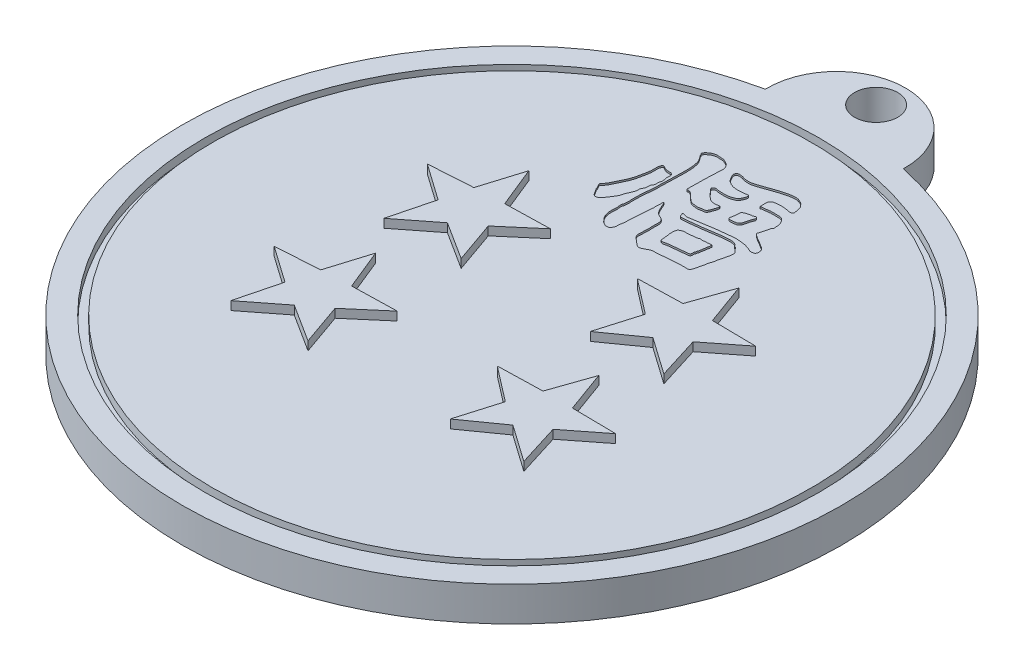
SolidWorks part; units mm, degrees
ref_plane "Front Plane" through (0, 0, 0) normal (0, 0, 1) x (1, 0, 0)
ref_plane "Top Plane" through (0, 0, 0) normal (0, 1, 0) x (1, 0, 0)
ref_plane "Right Plane" through (0, 0, 0) normal (1, 0, 0) x (0, 0, -1)
sketch "Sketch1" plane through (0, 0, 0) normal (0, 1, 0) x (1, 0, 0)
  line L0 (72.6998, 334.9365) -> (606.0331, 334.9365) construction
  line L11 (9.9855, -19.0663) -> (11.8306, -12.8124)
  line L12 (11.8306, -12.8124) -> (6.6838, -8.8503)
  line L13 (6.6838, -8.8503) -> (13.2484, -8.6755)
  line L14 (13.2484, -8.6755) -> (15.3732, -2.5828)
  line L15 (15.3732, -2.5828) -> (17.5873, -8.6755)
  line L16 (17.5873, -8.6755) -> (24.0432, -8.7629)
  line L17 (24.0432, -8.7629) -> (18.8692, -12.8124)
  line L18 (18.8692, -12.8124) -> (20.8153, -19.0663)
  line L19 (20.8153, -19.0663) -> (15.3732, -15.2382)
  line L20 (15.3732, -15.2382) -> (9.9855, -19.0663)
  line L21 (-4.1182, 14.4191) -> (1.9132, 14.499) construction
  line L22 (-1.1025, 14.459) -> (0, -28.999) construction
  line L33 (-21.2921, -20.1346) -> (-16.0512, -16.0354)
  line L34 (-19.6657, -13.79) -> (-21.2921, -20.1346)
  line L35 (-25.0384, -10.0081) -> (-19.6657, -13.79)
  line L36 (-18.5952, -9.5934) -> (-25.0384, -10.0081)
  line L37 (-16.6929, -3.3963) -> (-18.5952, -9.5934)
  line L38 (-14.2619, -9.3734) -> (-16.6929, -3.3963)
  line L39 (-7.6968, -9.2151) -> (-14.2619, -9.3734)
  line L40 (-12.6361, -13.4331) -> (-7.6968, -9.2151)
  line L41 (-10.4763, -19.5854) -> (-12.6361, -13.4331)
  line L42 (-16.0512, -16.0354) -> (-10.4763, -19.5854)
  line L43 (9.1329, 2.4208) -> (10.978, 8.6747)
  line L44 (10.978, 8.6747) -> (5.8312, 12.6368)
  line L45 (5.8312, 12.6368) -> (12.3958, 12.8116)
  line L46 (12.3958, 12.8116) -> (14.5206, 18.9043)
  line L47 (14.5206, 18.9043) -> (16.7347, 12.8116)
  line L48 (16.7347, 12.8116) -> (23.1906, 12.7242)
  line L49 (23.1906, 12.7242) -> (18.0166, 8.6747)
  line L50 (18.0166, 8.6747) -> (19.9627, 2.4208)
  line L51 (19.9627, 2.4208) -> (14.5206, 6.2489)
  line L52 (14.5206, 6.2489) -> (9.1329, 2.4208)
  line L53 (-20.5145, 1.6585) -> (-15.2735, 5.7576)
  line L54 (-18.888, 8.0031) -> (-20.5145, 1.6585)
  line L55 (-24.2607, 11.785) -> (-18.888, 8.0031)
  line L56 (-17.8175, 12.1996) -> (-24.2607, 11.785)
  line L57 (-15.9152, 18.3968) -> (-17.8175, 12.1996)
  line L58 (-13.4842, 12.4197) -> (-15.9152, 18.3968)
  line L59 (-6.9191, 12.5779) -> (-13.4842, 12.4197)
  line L60 (-11.8585, 8.36) -> (-6.9191, 12.5779)
  line L61 (-9.6986, 2.2076) -> (-11.8585, 8.36)
  line L62 (-15.2735, 5.7576) -> (-9.6986, 2.2076)
  circle A0 centre (0, 0) radius 48.586
  circle A1 centre (0, 0) radius 45.2612
  point P6 (0, 0)
  point P32 (0, -28.999)
sketch "Sketch2" plane through (0, 0, 0) normal (0, 1, 0) x (1, 0, 0)
  circle A0 centre (0, 0) radius 48.586 construction
  circle A1 centre (0, 0) radius 48.586
extrude "Boss-Extrude1" add sketch "Sketch2" along normal blind 5.08 contours A1
sketch "Sketch3" plane through (0, 5.08, 0) normal (0, 1, 0) x (1, 0, 0)
  circle A0 centre (0, 0) radius 44.1145 construction
  circle A1 centre (0, 0) radius 45.2612 construction
  circle A2 centre (0, 0) radius 44.1145
  circle A3 centre (0, 0) radius 45.2612
extrude "Cut-Extrude1" cut sketch "Sketch3" against normal blind 1.27
sketch "Sketch5" plane through (0, 5.08, 0) normal (0, 1, 0) x (1, 0, 0)
  line L0 (19.9627, 2.4208) -> (14.5206, 6.2489) construction
  line L1 (18.0166, 8.6747) -> (19.9627, 2.4208) construction
  line L2 (23.1906, 12.7242) -> (18.0166, 8.6747) construction
  line L3 (16.7347, 12.8116) -> (23.1906, 12.7242) construction
  line L4 (14.5206, 18.9043) -> (16.7347, 12.8116) construction
  line L5 (12.3958, 12.8116) -> (14.5206, 18.9043) construction
  line L6 (5.8312, 12.6368) -> (12.3958, 12.8116) construction
  line L7 (10.978, 8.6747) -> (5.8312, 12.6368) construction
  line L8 (9.1329, 2.4208) -> (10.978, 8.6747) construction
  line L9 (14.5206, 6.2489) -> (9.1329, 2.4208) construction
  line L10 (13.2484, -8.6755) -> (15.3732, -2.5828) construction
  line L11 (15.3732, -2.5828) -> (17.5873, -8.6755) construction
  line L12 (17.5873, -8.6755) -> (24.0432, -8.7629) construction
  line L13 (24.0432, -8.7629) -> (18.8692, -12.8124) construction
  line L14 (18.8692, -12.8124) -> (20.8153, -19.0663) construction
  line L15 (20.8153, -19.0663) -> (15.3732, -15.2382) construction
  line L16 (15.3732, -15.2382) -> (9.9855, -19.0663) construction
  line L17 (9.9855, -19.0663) -> (11.8306, -12.8124) construction
  line L18 (11.8306, -12.8124) -> (6.6838, -8.8503) construction
  line L19 (6.6838, -8.8503) -> (13.2484, -8.6755) construction
  line L20 (-7.6968, -9.2151) -> (-14.2619, -9.3734) construction
  line L21 (-12.6361, -13.4331) -> (-7.6968, -9.2151) construction
  line L22 (-10.4763, -19.5854) -> (-12.6361, -13.4331) construction
  line L23 (-16.0512, -16.0354) -> (-10.4763, -19.5854) construction
  line L24 (-21.2921, -20.1346) -> (-16.0512, -16.0354) construction
  line L25 (-19.6657, -13.79) -> (-21.2921, -20.1346) construction
  line L26 (-25.0384, -10.0081) -> (-19.6657, -13.79) construction
  line L27 (-18.5952, -9.5934) -> (-25.0384, -10.0081) construction
  line L28 (-16.6929, -3.3963) -> (-18.5952, -9.5934) construction
  line L29 (-14.2619, -9.3734) -> (-16.6929, -3.3963) construction
  line L30 (-15.2735, 5.7576) -> (-9.6986, 2.2076) construction
  line L31 (-9.6986, 2.2076) -> (-11.8585, 8.36) construction
  line L32 (-11.8585, 8.36) -> (-6.9191, 12.5779) construction
  line L33 (-6.9191, 12.5779) -> (-13.4842, 12.4197) construction
  line L34 (-13.4842, 12.4197) -> (-15.9152, 18.3968) construction
  line L35 (-15.9152, 18.3968) -> (-17.8175, 12.1996) construction
  line L36 (-17.8175, 12.1996) -> (-24.2607, 11.785) construction
  line L37 (-24.2607, 11.785) -> (-18.888, 8.0031) construction
  line L38 (-18.888, 8.0031) -> (-20.5145, 1.6585) construction
  line L39 (-20.5145, 1.6585) -> (-15.2735, 5.7576) construction
  line L40 (19.9627, 2.4208) -> (14.5206, 6.2489)
  line L41 (18.0166, 8.6747) -> (19.9627, 2.4208)
  line L42 (23.1906, 12.7242) -> (18.0166, 8.6747)
  line L43 (16.7347, 12.8116) -> (23.1906, 12.7242)
  line L44 (14.5206, 18.9043) -> (16.7347, 12.8116)
  line L45 (12.3958, 12.8116) -> (14.5206, 18.9043)
  line L46 (5.8312, 12.6368) -> (12.3958, 12.8116)
  line L47 (10.978, 8.6747) -> (5.8312, 12.6368)
  line L48 (9.1329, 2.4208) -> (10.978, 8.6747)
  line L49 (14.5206, 6.2489) -> (9.1329, 2.4208)
  line L50 (13.2484, -8.6755) -> (15.3732, -2.5828)
  line L51 (15.3732, -2.5828) -> (17.5873, -8.6755)
  line L52 (17.5873, -8.6755) -> (24.0432, -8.7629)
  line L53 (24.0432, -8.7629) -> (18.8692, -12.8124)
  line L54 (18.8692, -12.8124) -> (20.8153, -19.0663)
  line L55 (20.8153, -19.0663) -> (15.3732, -15.2382)
  line L56 (15.3732, -15.2382) -> (9.9855, -19.0663)
  line L57 (9.9855, -19.0663) -> (11.8306, -12.8124)
  line L58 (11.8306, -12.8124) -> (6.6838, -8.8503)
  line L59 (6.6838, -8.8503) -> (13.2484, -8.6755)
  line L60 (-7.6968, -9.2151) -> (-14.2619, -9.3734)
  line L61 (-12.6361, -13.4331) -> (-7.6968, -9.2151)
  line L62 (-10.4763, -19.5854) -> (-12.6361, -13.4331)
  line L63 (-16.0512, -16.0354) -> (-10.4763, -19.5854)
  line L64 (-21.2921, -20.1346) -> (-16.0512, -16.0354)
  line L65 (-19.6657, -13.79) -> (-21.2921, -20.1346)
  line L66 (-25.0384, -10.0081) -> (-19.6657, -13.79)
  line L67 (-18.5952, -9.5934) -> (-25.0384, -10.0081)
  line L68 (-16.6929, -3.3963) -> (-18.5952, -9.5934)
  line L69 (-14.2619, -9.3734) -> (-16.6929, -3.3963)
  line L70 (-15.2735, 5.7576) -> (-9.6986, 2.2076)
  line L71 (-9.6986, 2.2076) -> (-11.8585, 8.36)
  line L72 (-11.8585, 8.36) -> (-6.9191, 12.5779)
  line L73 (-6.9191, 12.5779) -> (-13.4842, 12.4197)
  line L74 (-13.4842, 12.4197) -> (-15.9152, 18.3968)
  line L75 (-15.9152, 18.3968) -> (-17.8175, 12.1996)
  line L76 (-17.8175, 12.1996) -> (-24.2607, 11.785)
  line L77 (-24.2607, 11.785) -> (-18.888, 8.0031)
  line L78 (-18.888, 8.0031) -> (-20.5145, 1.6585)
  line L79 (-20.5145, 1.6585) -> (-15.2735, 5.7576)
extrude "Boss-Extrude4" add sketch "Sketch5" along normal blind 1.27
sketch "Sketch6" plane through (0, 0, 0) normal (0, -1, 0) x (1, 0, 0)
  line L0 (0, 0) -> (0, -48.586) construction
  line L1 (0, -48.586) -> (0, -53.666) construction
  line L2 (10.16, -47.5119) -> (0, -48.586) construction
  line L3 (0, -48.586) -> (-10.16, -47.5119) construction
  circle A0 centre (0, 0) radius 48.586 construction
  circle A1 centre (0, -53.666) radius 3.175
  arc A2 (10.16, -47.5119) -> (-10.16, -47.5119) centre (0, -47.8316) cw
  circle M5 centre (0, 0) radius 48.586
  dimension "D1" = 6.35
  dimension "D4" = 10.165
  dimension "D2" = 5.08
  dimension "D3" = 10.16
extrude "Boss-Extrude5" add sketch "Sketch6" against normal up to surface (5.08 mm away) contours A2 A1 M5 up to face at (0, 5.08, 45.2612)
sketch "Sketch7" plane through (0, 5.08, 0) normal (0, 1, 0) x (1, 0, 0)
  line L0 (140.8867, 493.3987) -> (794.2201, 493.3987) construction
  spline S0 degree 3 poles (-3.7836, 35.2045) (-3.5089, 35.0981) (-3.2915, 34.8741) (-3.1389, 34.5991) (-3.0052, 34.177) (-3.1249, 33.6304) (-3.0644, 32.9308) (-3.1263, 32.1641) (-3.1777, 31.3954) (-3.1455, 30.6787) (-3.1644, 30.0405) (-3.1763, 29.4923) (-3.202, 29.1508) (-3.1534, 28.8256) (-2.9198, 28.9809) (-2.7009, 28.8609) (-2.4188, 28.7675) (-2.1857, 28.4675) (-1.8669, 28.2384) (-1.5861, 27.908) (-1.2854, 27.7054) (-0.9431, 27.5455) (-0.5328, 27.5044) (-0.031, 27.4441) (0.4097, 27.5927) (0.7344, 27.5886) (0.9698, 27.6572) (1.0884, 27.8586) (1.2713, 28.3125) (1.7457, 29.4886) (0.9478, 29.1003) (0.6202, 29.1708) (0.3204, 29.1642) (0.0135, 29.2701) (-0.3132, 29.5366) (-0.662, 29.8389) (-0.9763, 30.2207) (-1.2818, 30.496) (-1.4556, 30.7183) (-1.5899, 31.0316) (-1.3014, 31.0599) (-1.1735, 31.2344) (-0.8941, 31.1356) (-0.609, 31.1185) (-0.1231, 31.0805) (0.3708, 31.0664) (0.9699, 31.128) (1.3837, 31.3549) (1.7867, 31.4497) (2.0412, 31.9201) (2.4685, 32.8608) (1.639, 32.6288) (1.1004, 32.6586) (0.5295, 32.5597) (0.1059, 32.6315) (-0.1765, 32.6823) (-0.3604, 32.8178) (-0.586, 32.8277) (-0.6821, 33.011) (-0.9456, 33.0333) (-1.0927, 33.2692) (-1.3119, 33.483) (-1.3974, 33.7818) (-1.5697, 34.0046) (-1.6727, 34.2764) (-1.6204, 34.5866) (-1.3062, 34.7622) (-0.9871, 34.7165) (-0.5973, 34.6782) (-0.2544, 34.4887) (0.1677, 34.5192) (0.6049, 34.445) (1.107, 34.6293) (1.689, 34.7699) (2.3144, 35.028) (3.0022, 35.1982) (3.5819, 35.4539) (4.093, 35.6101) (4.528, 35.7079) (4.9831, 35.8469) (5.4125, 35.911) (5.8519, 35.9535) (6.2942, 35.9184) (6.6881, 35.7437) (7.0317, 35.5601) (7.2316, 35.3164) (7.4687, 35.0799) (7.5771, 34.7503) (7.6769, 34.4243) (7.6967, 34.1301) (7.7854, 33.8634) (7.6396, 33.7259) (7.511, 33.5979) (7.2893, 33.5981) (7.0031, 33.6726) (6.61, 33.7351) (6.1138, 33.7866) (5.6119, 33.7841) (5.2065, 33.7079) (4.9316, 33.7083) (4.7359, 33.658) (4.6548, 33.5059) (4.5413, 33.3836) (4.4021, 33.2285) (4.3935, 32.9984) (4.4246, 32.7765) (4.4008, 32.5136) (4.4427, 32.33) (4.3939, 32.0301) (4.6138, 32.2069) (4.8511, 32.1759) (5.1271, 32.2551) (5.4716, 32.2584) (5.7784, 32.3491) (6.2025, 32.3275) (6.592, 32.3161) (6.9492, 32.3163) (7.2031, 32.3201) (7.3884, 32.2565) (7.5948, 32.148) (7.7958, 31.9598) (7.9926, 31.6202) (8.1568, 31.284) (8.1937, 30.9204) (8.1837, 30.6376) (8.2599, 30.3373) (8.0223, 30.1491) (8.0065, 29.8231) (7.8875, 29.5105) (7.8495, 29.2056) (7.7193, 28.9715) (7.7212, 28.7417) (7.5927, 28.5614) (7.6486, 28.3243) (7.8482, 28.165) (8.1225, 28.0321) (8.3693, 27.8339) (8.6976, 27.6764) (9.0026, 27.4911) (9.2854, 27.3028) (9.5469, 27.134) (9.8317, 27.0114) (9.9823, 26.7634) (10.1584, 26.5687) (10.1041, 26.366) (10.2076, 26.1888) (10.1424, 25.9543) (10.0037, 25.7445) (9.6875, 25.6829) (9.3579, 25.6793) (9.0323, 25.8649) (8.6536, 25.9923) (8.2078, 26.1509) (7.6978, 26.2033) (7.231, 26.2679) (6.7409, 26.2982) (6.2694, 26.3102) (5.8148, 26.2001) (5.3369, 26.1804) (4.8125, 26.0902) (4.2287, 26.0241) (3.6571, 25.9649) (3.0068, 25.7729) (2.351, 25.7201) (1.6659, 25.6014) (1.1056, 25.4963) (0.5496, 25.4422) (0.1359, 25.3767) (-0.5654, 25.7212) (-0.3203, 25.3488) (-0.3219, 25.1436) (-0.1782, 25.0022) (0.0486, 24.9061) (0.371, 25.0185) (0.8278, 24.988) (1.3886, 25.0709) (2.01, 25.1408) (2.5683, 25.213) (3.1003, 25.2557) (3.613, 25.3782) (4.2241, 25.4428) (4.9256, 25.5576) (5.5898, 25.6342) (6.2127, 25.6733) (6.6591, 25.7001) (7.0265, 25.6562) (7.2948, 25.5264) (7.5452, 25.4097) (7.6448, 25.0287) (7.8517, 25.1977) (8.0341, 24.8026) (8.2776, 24.5969) (8.5994, 24.2972) (8.4928, 23.9664) (8.5302, 23.6729) (8.3886, 23.3897) (8.3664, 23.054) (8.2572, 22.7223) (8.1944, 22.3723) (8.0791, 22.0634) (8.0772, 21.7102) (7.9417, 21.3449) (7.8043, 20.9446) (7.7949, 20.4858) (7.626, 20.0909) (7.5704, 19.6728) (7.4456, 19.3466) (7.3976, 19.0119) (7.0875, 18.7779) (6.6061, 18.8696) (6.0046, 18.8325) (5.3649, 18.8274) (4.7751, 18.7542) (4.2395, 18.7201) (3.7264, 18.6612) (3.2156, 18.6669) (2.6512, 18.5363) (2.073, 18.6159) (1.5751, 18.3477) (1.2134, 18.1683) (0.8773, 17.9729) (0.476, 17.99) (0.1521, 18.2617) (-0.1789, 18.5315) (-0.4612, 18.7961) (-0.7369, 18.9744) (-0.8964, 19.2182) (-1.07, 19.5493) (-0.9938, 19.979) (-0.985, 20.6432) (-0.9358, 21.3081) (-1.0159, 22.0378) (-0.9547, 22.5103) (-0.9993, 22.9089) (-1.1533, 23.1813) (-1.4287, 23.3935) (-1.7581, 23.4837) (-2.0732, 23.675) (-2.3135, 23.8827) (-2.4297, 24.1145) (-2.5757, 24.3159) (-2.6661, 24.5097) (-2.7444, 24.7109) (-2.827, 24.86) (-2.9175, 25.033) (-2.9487, 25.2188) (-3.0507, 25.3649) (-3.0995, 25.4726) (-3.2008, 25.6233) (-3.2595, 25.3359) (-3.2231, 25.165) (-3.2783, 24.9198) (-3.239, 24.6957) (-3.3204, 24.4607) (-3.231, 24.2223) (-3.2847, 23.9347) (-3.2968, 23.6148) (-3.3631, 23.2553) (-3.3385, 22.9202) (-3.3955, 22.5735) (-3.3877, 22.2285) (-3.4402, 21.5667) (-3.5388, 20.9257) (-3.5077, 20.2114) (-3.5835, 19.7707) (-3.6865, 19.3421) (-3.6325, 18.9841) (-3.7267, 18.6813) (-3.9059, 18.5239) (-4.02, 18.3198) (-4.2673, 18.3193) (-4.5231, 18.2732) (-4.7611, 18.4038) (-4.951, 18.5168) (-5.1295, 18.6346) (-5.2659, 18.7905) (-5.4184, 18.9669) (-5.5883, 19.1346) (-5.7036, 19.3456) (-5.8201, 19.5258) (-5.8998, 19.6922) (-5.8811, 19.8482) (-5.985, 19.9875) (-6.0122, 20.188) (-6.0307, 20.3608) (-6.0475, 20.5815) (-6.0126, 20.8376) (-6.0503, 21.209) (-5.9529, 21.6587) (-6.1399, 22.0929) (-5.9551, 22.4219) (-5.951, 22.6953) (-5.9095, 22.9494) (-5.888, 23.2158) (-5.9588, 23.4669) (-5.921, 23.8135) (-5.9203, 24.232) (-5.8852, 24.7472) (-5.9388, 25.304) (-5.8255, 25.8185) (-5.7694, 26.2347) (-5.7937, 26.5924) (-5.707, 26.9982) (-5.7533, 27.425) (-5.7443, 27.945) (-5.7423, 28.586) (-5.6856, 29.3486) (-5.6956, 30.159) (-5.6354, 30.8559) (-5.6303, 31.5356) (-5.6898, 32.08) (-5.6925, 32.5715) (-5.8106, 32.9005) (-5.8158, 33.2034) (-5.9579, 33.3884) (-6.0124, 33.6001) (-6.1451, 33.7114) (-6.1636, 33.8538) (-6.3005, 33.9334) (-6.3532, 34.0964) (-6.4992, 34.2186) (-6.5145, 34.4046) (-6.7359, 34.5085) (-6.6201, 34.8362) (-6.4403, 35.0915) (-6.1304, 35.1585) (-5.9861, 35.3681) (-5.7104, 35.4732) (-5.2967, 35.5698) (-4.8338, 35.4962) (-4.3902, 35.5063) (-4.0435, 35.3811) (-3.7836, 35.2045) (-3.5089, 35.0981) (-3.2915, 34.8741) knots -0.007629 -0.004974 -0.00202 0 0.002078 0.00539 0.007596 0.012664 0.018527 0.024632 0.031294 0.037247 0.041978 0.046955 0.050054 0.051343 0.053087 0.05461 0.057236 0.060177 0.06353 0.066759 0.070627 0.072234 0.075881 0.080535 0.084354 0.086894 0.088469 0.089986 0.092213 0.101638 0.105781 0.107664 0.109953 0.112967 0.115302 0.120151 0.124134 0.127363 0.129875 0.131556 0.133822 0.134867 0.136425 0.139965 0.142254 0.148126 0.152082 0.15655 0.159796 0.161153 0.169822 0.172857 0.177924 0.183967 0.186354 0.188372 0.190856 0.191688 0.193598 0.195069 0.197606 0.199809 0.202509 0.204894 0.206583 0.209522 0.211524 0.214663 0.217116 0.221051 0.223752 0.227225 0.231645 0.236403 0.241837 0.248003 0.253567 0.257181 0.260963 0.264392 0.268722 0.271472 0.275121 0.279325 0.281865 0.284461 0.286912 0.289891 0.292722 0.29512 0.297256 0.298727 0.299588 0.301625 0.303558 0.306923 0.311207 0.315693 0.319066 0.321125 0.322475 0.323625 0.325105 0.326596 0.328508 0.330376 0.332145 0.334642 0.335779 0.33734 0.338801 0.341991 0.343955 0.347191 0.349623 0.354205 0.356668 0.358312 0.36033 0.361333 0.363972 0.366855 0.370855 0.372927 0.375596 0.377968 0.379514 0.382259 0.385407 0.387705 0.389614 0.391787 0.393047 0.394736 0.397051 0.399031 0.402158 0.404662 0.40785 0.410823 0.412897 0.415454 0.41807 0.419914 0.421322 0.422715 0.424585 0.426896 0.428359 0.432153 0.434642 0.437303 0.44187 0.446066 0.449702 0.453317 0.458004 0.461061 0.464615 0.469585 0.473968 0.47889 0.483506 0.490362 0.494819 0.500345 0.504389 0.507832 0.512267 0.51431 0.515379 0.517345 0.518646 0.521234 0.525112 0.529774 0.534928 0.540319 0.543444 0.547871 0.553084 0.558351 0.565136 0.569305 0.573514 0.575982 0.578211 0.580564 0.583245 0.58354 0.58645 0.589613 0.593116 0.595325 0.597453 0.600191 0.602709 0.605564 0.608626 0.611343 0.613481 0.617095 0.620709 0.623708 0.628093 0.630978 0.633875 0.636611 0.638852 0.642405 0.64787 0.653658 0.657868 0.662301 0.666688 0.670408 0.674644 0.680712 0.683893 0.688082 0.690648 0.693152 0.697251 0.700517 0.703608 0.706647 0.708327 0.710639 0.715525 0.718355 0.726893 0.731611 0.736104 0.738401 0.741236 0.743423 0.74668 0.749403 0.752349 0.754218 0.755643 0.758384 0.759377 0.760881 0.762523 0.764083 0.7654 0.766666 0.767317 0.768793 0.770742 0.772663 0.774459 0.776238 0.778438 0.780316 0.783233 0.786234 0.789139 0.791329 0.794733 0.797491 0.807452 0.810409 0.814791 0.818289 0.820977 0.823491 0.825536 0.826765 0.828815 0.83089 0.833058 0.835073 0.836341 0.838215 0.840064 0.842022 0.843972 0.845849 0.847283 0.848322 0.849473 0.851289 0.853142 0.85372 0.856658 0.859368 0.862718 0.867703 0.869532 0.871501 0.874238 0.875821 0.877931 0.880462 0.884195 0.888118 0.892988 0.897656 0.900826 0.903157 0.906314 0.910795 0.913484 0.918951 0.926355 0.932042 0.938613 0.943337 0.948511 0.951933 0.955159 0.956929 0.959081 0.960609 0.962114 0.963056 0.963808 0.965719 0.966996 0.968222 0.969897 0.971784 0.975261 0.977403 0.978925 0.981171 0.984323 0.989207 0.992371 0.995026 0.99798 1 1.002078 1.00539 1.007596 only from (-3.5208, 35.0839) to (-3.5208, 35.0839)
  spline S1 degree 3 poles (1.6683, 20.4631) (1.357, 20.55) (1.3868, 20.9287) (1.309, 21.2902) (1.3047, 21.6543) (1.2156, 21.9873) (1.2463, 22.2874) (1.1854, 22.5858) (1.298, 22.8281) (1.3278, 23.1183) (1.6221, 23.1562) (1.8189, 23.3631) (2.2465, 23.3511) (2.6933, 23.3214) (3.1364, 23.4183) (3.5113, 23.4616) (3.877, 23.4542) (4.2064, 23.692) (4.4631, 23.5047) (4.6995, 23.6032) (4.9347, 23.6277) (5.1929, 23.5991) (5.4145, 23.688) (5.6013, 23.677) (5.9143, 23.6652) (5.7283, 23.5369) (5.8184, 23.3552) (5.7491, 23.1584) (5.6881, 22.9472) (5.675, 22.7403) (5.634, 22.5249) (5.6248, 22.3466) (5.5851, 22.1818) (5.5616, 22.0752) (5.5766, 21.933) (5.4405, 21.8302) (5.5102, 21.629) (5.3727, 21.4889) (5.4006, 21.3199) (5.3966, 21.1721) (5.3875, 21.0087) (5.2266, 20.8849) (5.0156, 20.8795) (4.793, 20.8494) (4.5965, 20.8184) (4.3809, 20.796) (4.1137, 20.7483) (3.7805, 20.74) (3.3812, 20.714) (2.9745, 20.6222) (2.5576, 20.6221) (2.2222, 20.5578) (1.9218, 20.4682) (1.6683, 20.4631) (1.357, 20.55) (1.3868, 20.9287) knots -0.05572 -0.036145 -0.012641 0 0.027242 0.053189 0.084692 0.104414 0.12725 0.149766 0.167459 0.185378 0.204991 0.222213 0.244933 0.291565 0.32141 0.342232 0.373373 0.400527 0.417412 0.432728 0.452372 0.468795 0.488895 0.499368 0.517227 0.522976 0.536231 0.553033 0.567391 0.583902 0.597725 0.614924 0.62239 0.634482 0.638436 0.652552 0.663845 0.678607 0.689258 0.69905 0.711439 0.722438 0.739144 0.756259 0.771362 0.782217 0.803259 0.830087 0.854363 0.889936 0.920013 0.94428 0.963855 0.987359 1 1.027242 1.053189 1.084692 only from (1.4502, 20.5475) to (1.4502, 20.5475)
  spline S2 degree 3 poles (3.7659, 29.9366) (3.7729, 29.7303) (3.7595, 29.4543) (3.6984, 29.0897) (3.6684, 28.7571) (3.5673, 28.543) (3.5985, 28.3349) (3.9305, 28.1836) (4.3427, 28.3001) (5.2436, 28.3282) (5.3027, 29.3702) (5.5279, 29.9803) (5.6713, 30.2438) (5.6098, 30.527) (5.3123, 30.5722) (5.1516, 30.3567) (4.8902, 30.4065) (4.6131, 30.3027) (4.2696, 30.2408) (3.9573, 30.121) (3.7659, 29.9366) (3.7729, 29.7303) (3.7595, 29.4543) knots -0.097797 -0.033473 -0.003749 0 0.05317 0.1134 0.156634 0.193344 0.211968 0.238222 0.331273 0.3939 0.590806 0.651018 0.679964 0.716019 0.753906 0.77624 0.820726 0.850878 0.902203 0.966527 0.996251 1 1.05317 1.1134 1.156634 only from (3.7689, 29.848) to (3.7689, 29.848)
  spline S3 degree 3 poles (-8.7326, 21.2793) (-9.1077, 21.2895) (-9.4234, 21.4851) (-9.5985, 21.8878) (-9.9662, 22.3131) (-10.0718, 22.7968) (-10.381, 23.178) (-10.1515, 23.4996) (-9.7625, 23.8817) (-9.4152, 24.7778) (-8.8706, 25.7618) (-8.5332, 26.7663) (-8.3159, 27.7776) (-8.1524, 28.6636) (-8.1913, 29.4503) (-8.1612, 29.8861) (-7.9779, 30.3512) (-7.4671, 30.0245) (-7.0266, 29.8176) (-6.4912, 29.9361) (-5.9931, 29.6357) (-6.2309, 28.997) (-5.913, 28.3115) (-6.189, 27.7021) (-6.0857, 27.1188) (-6.4404, 26.8269) (-6.3585, 26.3655) (-6.4315, 25.9512) (-6.7414, 25.5853) (-6.6223, 25.0791) (-6.8301, 24.6438) (-7.0108, 24.1868) (-7.2142, 23.7958) (-7.2857, 23.3183) (-7.4814, 22.9298) (-7.7975, 22.4996) (-8.0447, 22.0113) (-8.4456, 21.6264) (-8.7326, 21.2793) (-9.1077, 21.2895) (-9.4234, 21.4851) knots -0.059376 -0.035133 -0.014631 0 0.013548 0.036066 0.060414 0.091586 0.107287 0.12096 0.140494 0.187251 0.252205 0.301519 0.336426 0.398913 0.429494 0.445215 0.465308 0.480869 0.515694 0.536316 0.555822 0.58406 0.616749 0.658056 0.671587 0.696786 0.711329 0.734817 0.75505 0.774467 0.80294 0.82105 0.844718 0.864716 0.888859 0.905395 0.940624 0.964867 0.985369 1 1.013548 1.036066 1.060414 only from (-9.1048, 21.3174) to (-9.1048, 21.3174)
sketch "Sketch8" plane through (0, 5.08, 0) normal (0, 1, 0) x (1, 0, 0)
  spline S0 degree 3 poles (1.3868, 20.9287) (1.357, 20.55) (1.6683, 20.4631) (1.9218, 20.4682) (2.2222, 20.5578) (2.5576, 20.6221) (2.9745, 20.6222) (3.3812, 20.714) (3.7805, 20.74) (4.1137, 20.7483) (4.3809, 20.796) (4.5965, 20.8184) (4.793, 20.8494) (5.0156, 20.8795) (5.2266, 20.8849) (5.3875, 21.0087) (5.3966, 21.1721) (5.4006, 21.3199) (5.3727, 21.4889) (5.5102, 21.629) (5.4405, 21.8302) (5.5766, 21.933) (5.5616, 22.0752) (5.5851, 22.1818) (5.6248, 22.3466) (5.634, 22.5249) (5.675, 22.7403) (5.6881, 22.9472) (5.7491, 23.1584) (5.8184, 23.3552) (5.7283, 23.5369) (5.9143, 23.6652) (5.6013, 23.677) (5.4145, 23.688) (5.1929, 23.5991) (4.9347, 23.6277) (4.6995, 23.6032) (4.4631, 23.5047) (4.2064, 23.692) (3.877, 23.4542) (3.5113, 23.4616) (3.1364, 23.4183) (2.6933, 23.3214) (2.2465, 23.3511) (1.8189, 23.3631) (1.6221, 23.1562) (1.3278, 23.1183) (1.298, 22.8281) (1.1854, 22.5858) (1.2463, 22.2874) (1.2156, 21.9873) (1.3047, 21.6543) (1.309, 21.2902) (1.3868, 20.9287) (1.357, 20.55) (1.6683, 20.4631) knots -0.084692 -0.053189 -0.027242 0 0.012641 0.036145 0.05572 0.079987 0.110064 0.145637 0.169913 0.196741 0.217783 0.228638 0.243741 0.260856 0.277562 0.288561 0.30095 0.310742 0.321393 0.336155 0.347448 0.361564 0.365518 0.37761 0.385076 0.402275 0.416098 0.432609 0.446967 0.463769 0.477024 0.482773 0.500632 0.511105 0.531205 0.547628 0.567272 0.582588 0.599473 0.626627 0.657768 0.67859 0.708435 0.755067 0.777787 0.795009 0.814622 0.832541 0.850234 0.87275 0.895586 0.915308 0.946811 0.972758 1 1.012641 1.036145 1.05572 only from (1.4502, 20.5475) to (1.4502, 20.5475) construction
  spline S1 degree 3 poles (3.7659, 29.9366) (3.7729, 29.7303) (3.7595, 29.4543) (3.6984, 29.0897) (3.6684, 28.7571) (3.5673, 28.543) (3.5985, 28.3349) (3.9305, 28.1836) (4.3427, 28.3001) (5.2436, 28.3282) (5.3027, 29.3702) (5.5279, 29.9803) (5.6713, 30.2438) (5.6098, 30.527) (5.3123, 30.5722) (5.1516, 30.3567) (4.8902, 30.4065) (4.6131, 30.3027) (4.2696, 30.2408) (3.9573, 30.121) (3.7659, 29.9366) (3.7729, 29.7303) (3.7595, 29.4543) knots -0.097797 -0.033473 -0.003749 0 0.05317 0.1134 0.156634 0.193344 0.211968 0.238222 0.331273 0.3939 0.590806 0.651018 0.679964 0.716019 0.753906 0.77624 0.820726 0.850878 0.902203 0.966527 0.996251 1 1.05317 1.1134 1.156634 only from (3.7689, 29.848) to (3.7689, 29.848) construction
  spline S2 degree 3 poles (-9.4234, 21.4851) (-9.1077, 21.2895) (-8.7326, 21.2793) (-8.4456, 21.6264) (-8.0447, 22.0113) (-7.7975, 22.4996) (-7.4814, 22.9298) (-7.2857, 23.3183) (-7.2142, 23.7958) (-7.0108, 24.1868) (-6.8301, 24.6438) (-6.6223, 25.0791) (-6.7414, 25.5853) (-6.4315, 25.9512) (-6.3585, 26.3655) (-6.4404, 26.8269) (-6.0857, 27.1188) (-6.189, 27.7021) (-5.913, 28.3115) (-6.2309, 28.997) (-5.9931, 29.6357) (-6.4912, 29.9361) (-7.0266, 29.8176) (-7.4671, 30.0245) (-7.9779, 30.3512) (-8.1612, 29.8861) (-8.1913, 29.4503) (-8.1524, 28.6636) (-8.3159, 27.7776) (-8.5332, 26.7663) (-8.8706, 25.7618) (-9.4152, 24.7778) (-9.7625, 23.8817) (-10.1515, 23.4996) (-10.381, 23.178) (-10.0718, 22.7968) (-9.9662, 22.3131) (-9.5985, 21.8878) (-9.4234, 21.4851) (-9.1077, 21.2895) (-8.7326, 21.2793) knots -0.060414 -0.036066 -0.013548 0 0.014631 0.035133 0.059376 0.094605 0.111141 0.135284 0.155282 0.17895 0.19706 0.225533 0.24495 0.265183 0.288671 0.303214 0.328413 0.341944 0.383251 0.41594 0.444178 0.463684 0.484306 0.519131 0.534692 0.554785 0.570506 0.601087 0.663574 0.698481 0.747795 0.812749 0.859506 0.87904 0.892713 0.908414 0.939586 0.963934 0.986452 1 1.014631 1.035133 1.059376 only from (-9.1048, 21.3174) to (-9.1048, 21.3174) construction
  spline S3 degree 3 poles (-3.2915, 34.8741) (-3.5089, 35.0981) (-3.7836, 35.2045) (-4.0435, 35.3811) (-4.3902, 35.5063) (-4.8338, 35.4962) (-5.2967, 35.5698) (-5.7104, 35.4732) (-5.9861, 35.3681) (-6.1304, 35.1585) (-6.4403, 35.0915) (-6.6201, 34.8362) (-6.7359, 34.5085) (-6.5145, 34.4046) (-6.4992, 34.2186) (-6.3532, 34.0964) (-6.3005, 33.9334) (-6.1636, 33.8538) (-6.1451, 33.7114) (-6.0124, 33.6001) (-5.9579, 33.3884) (-5.8158, 33.2034) (-5.8106, 32.9005) (-5.6925, 32.5715) (-5.6898, 32.08) (-5.6303, 31.5356) (-5.6354, 30.8559) (-5.6956, 30.159) (-5.6856, 29.3486) (-5.7423, 28.586) (-5.7443, 27.945) (-5.7533, 27.425) (-5.707, 26.9982) (-5.7937, 26.5924) (-5.7694, 26.2347) (-5.8255, 25.8185) (-5.9388, 25.304) (-5.8852, 24.7472) (-5.9203, 24.232) (-5.921, 23.8135) (-5.9588, 23.4669) (-5.888, 23.2158) (-5.9095, 22.9494) (-5.951, 22.6953) (-5.9551, 22.4219) (-6.1399, 22.0929) (-5.9529, 21.6587) (-6.0503, 21.209) (-6.0126, 20.8376) (-6.0475, 20.5815) (-6.0307, 20.3608) (-6.0122, 20.188) (-5.985, 19.9875) (-5.8811, 19.8482) (-5.8998, 19.6922) (-5.8201, 19.5258) (-5.7036, 19.3456) (-5.5883, 19.1346) (-5.4184, 18.9669) (-5.2659, 18.7905) (-5.1295, 18.6346) (-4.951, 18.5168) (-4.7611, 18.4038) (-4.5231, 18.2732) (-4.2673, 18.3193) (-4.02, 18.3198) (-3.9059, 18.5239) (-3.7267, 18.6813) (-3.6325, 18.9841) (-3.6865, 19.3421) (-3.5835, 19.7707) (-3.5077, 20.2114) (-3.5388, 20.9257) (-3.4402, 21.5667) (-3.3877, 22.2285) (-3.3955, 22.5735) (-3.3385, 22.9202) (-3.3631, 23.2553) (-3.2968, 23.6148) (-3.2847, 23.9347) (-3.231, 24.2223) (-3.3204, 24.4607) (-3.239, 24.6957) (-3.2783, 24.9198) (-3.2231, 25.165) (-3.2595, 25.3359) (-3.2008, 25.6233) (-3.0995, 25.4726) (-3.0507, 25.3649) (-2.9487, 25.2188) (-2.9175, 25.033) (-2.827, 24.86) (-2.7444, 24.7109) (-2.6661, 24.5097) (-2.5757, 24.3159) (-2.4297, 24.1145) (-2.3135, 23.8827) (-2.0732, 23.675) (-1.7581, 23.4837) (-1.4287, 23.3935) (-1.1533, 23.1813) (-0.9993, 22.9089) (-0.9547, 22.5103) (-1.0159, 22.0378) (-0.9358, 21.3081) (-0.985, 20.6432) (-0.9938, 19.979) (-1.07, 19.5493) (-0.8964, 19.2182) (-0.7369, 18.9744) (-0.4612, 18.7961) (-0.1789, 18.5315) (0.1521, 18.2617) (0.476, 17.99) (0.8773, 17.9729) (1.2134, 18.1683) (1.5751, 18.3477) (2.073, 18.6159) (2.6512, 18.5363) (3.2156, 18.6669) (3.7264, 18.6612) (4.2395, 18.7201) (4.7751, 18.7542) (5.3649, 18.8274) (6.0046, 18.8325) (6.6061, 18.8696) (7.0875, 18.7779) (7.3976, 19.0119) (7.4456, 19.3466) (7.5704, 19.6728) (7.626, 20.0909) (7.7949, 20.4858) (7.8043, 20.9446) (7.9417, 21.3449) (8.0772, 21.7102) (8.0791, 22.0634) (8.1944, 22.3723) (8.2572, 22.7223) (8.3664, 23.054) (8.3886, 23.3897) (8.5302, 23.6729) (8.4928, 23.9664) (8.5994, 24.2972) (8.2776, 24.5969) (8.0341, 24.8026) (7.8517, 25.1977) (7.6448, 25.0287) (7.5452, 25.4097) (7.2948, 25.5264) (7.0265, 25.6562) (6.6591, 25.7001) (6.2127, 25.6733) (5.5898, 25.6342) (4.9256, 25.5576) (4.2241, 25.4428) (3.613, 25.3782) (3.1003, 25.2557) (2.5683, 25.213) (2.01, 25.1408) (1.3886, 25.0709) (0.8278, 24.988) (0.371, 25.0185) (0.0486, 24.9061) (-0.1782, 25.0022) (-0.3219, 25.1436) (-0.3203, 25.3488) (-0.5654, 25.7212) (0.1359, 25.3767) (0.5496, 25.4422) (1.1056, 25.4963) (1.6659, 25.6014) (2.351, 25.7201) (3.0068, 25.7729) (3.6571, 25.9649) (4.2287, 26.0241) (4.8125, 26.0902) (5.3369, 26.1804) (5.8148, 26.2001) (6.2694, 26.3102) (6.7409, 26.2982) (7.231, 26.2679) (7.6978, 26.2033) (8.2078, 26.1509) (8.6536, 25.9923) (9.0323, 25.8649) (9.3579, 25.6793) (9.6875, 25.6829) (10.0037, 25.7445) (10.1424, 25.9543) (10.2076, 26.1888) (10.1041, 26.366) (10.1584, 26.5687) (9.9823, 26.7634) (9.8317, 27.0114) (9.5469, 27.134) (9.2854, 27.3028) (9.0026, 27.4911) (8.6976, 27.6764) (8.3693, 27.8339) (8.1225, 28.0321) (7.8482, 28.165) (7.6486, 28.3243) (7.5927, 28.5614) (7.7212, 28.7417) (7.7193, 28.9715) (7.8495, 29.2056) (7.8875, 29.5105) (8.0065, 29.8231) (8.0223, 30.1491) (8.2599, 30.3373) (8.1837, 30.6376) (8.1937, 30.9204) (8.1568, 31.284) (7.9926, 31.6202) (7.7958, 31.9598) (7.5948, 32.148) (7.3884, 32.2565) (7.2031, 32.3201) (6.9492, 32.3163) (6.592, 32.3161) (6.2025, 32.3275) (5.7784, 32.3491) (5.4716, 32.2584) (5.1271, 32.2551) (4.8511, 32.1759) (4.6138, 32.2069) (4.3939, 32.0301) (4.4427, 32.33) (4.4008, 32.5136) (4.4246, 32.7765) (4.3935, 32.9984) (4.4021, 33.2285) (4.5413, 33.3836) (4.6548, 33.5059) (4.7359, 33.658) (4.9316, 33.7083) (5.2065, 33.7079) (5.6119, 33.7841) (6.1138, 33.7866) (6.61, 33.7351) (7.0031, 33.6726) (7.2893, 33.5981) (7.511, 33.5979) (7.6396, 33.7259) (7.7854, 33.8634) (7.6967, 34.1301) (7.6769, 34.4243) (7.5771, 34.7503) (7.4687, 35.0799) (7.2316, 35.3164) (7.0317, 35.5601) (6.6881, 35.7437) (6.2942, 35.9184) (5.8519, 35.9535) (5.4125, 35.911) (4.9831, 35.8469) (4.528, 35.7079) (4.093, 35.6101) (3.5819, 35.4539) (3.0022, 35.1982) (2.3144, 35.028) (1.689, 34.7699) (1.107, 34.6293) (0.6049, 34.445) (0.1677, 34.5192) (-0.2544, 34.4887) (-0.5973, 34.6782) (-0.9871, 34.7165) (-1.3062, 34.7622) (-1.6204, 34.5866) (-1.6727, 34.2764) (-1.5697, 34.0046) (-1.3974, 33.7818) (-1.3119, 33.483) (-1.0927, 33.2692) (-0.9456, 33.0333) (-0.6821, 33.011) (-0.586, 32.8277) (-0.3604, 32.8178) (-0.1765, 32.6823) (0.1059, 32.6315) (0.5295, 32.5597) (1.1004, 32.6586) (1.639, 32.6288) (2.4685, 32.8608) (2.0412, 31.9201) (1.7867, 31.4497) (1.3837, 31.3549) (0.9699, 31.128) (0.3708, 31.0664) (-0.1231, 31.0805) (-0.609, 31.1185) (-0.8941, 31.1356) (-1.1735, 31.2344) (-1.3014, 31.0599) (-1.5899, 31.0316) (-1.4556, 30.7183) (-1.2818, 30.496) (-0.9763, 30.2207) (-0.662, 29.8389) (-0.3132, 29.5366) (0.0135, 29.2701) (0.3204, 29.1642) (0.6202, 29.1708) (0.9478, 29.1003) (1.7457, 29.4886) (1.2713, 28.3125) (1.0884, 27.8586) (0.9698, 27.6572) (0.7344, 27.5886) (0.4097, 27.5927) (-0.031, 27.4441) (-0.5328, 27.5044) (-0.9431, 27.5455) (-1.2854, 27.7054) (-1.5861, 27.908) (-1.8669, 28.2384) (-2.1857, 28.4675) (-2.4188, 28.7675) (-2.7009, 28.8609) (-2.9198, 28.9809) (-3.1534, 28.8256) (-3.202, 29.1508) (-3.1763, 29.4923) (-3.1644, 30.0405) (-3.1455, 30.6787) (-3.1777, 31.3954) (-3.1263, 32.1641) (-3.0644, 32.9308) (-3.1249, 33.6304) (-3.0052, 34.177) (-3.1389, 34.5991) (-3.2915, 34.8741) (-3.5089, 35.0981) (-3.7836, 35.2045) knots -0.007596 -0.00539 -0.002078 0 0.00202 0.004974 0.007629 0.010793 0.015677 0.018829 0.021075 0.022597 0.024739 0.028216 0.030103 0.031778 0.033004 0.034281 0.036192 0.036944 0.037886 0.039391 0.040919 0.043071 0.044841 0.048067 0.051489 0.056663 0.061387 0.067958 0.073645 0.081049 0.086516 0.089205 0.093686 0.096843 0.099174 0.102344 0.107012 0.111882 0.115805 0.119538 0.122069 0.124179 0.125762 0.128499 0.130468 0.132297 0.137282 0.140632 0.143342 0.14628 0.146858 0.148711 0.150527 0.151678 0.152717 0.154151 0.156028 0.157978 0.159936 0.161785 0.163659 0.164927 0.166942 0.16911 0.171185 0.173235 0.174464 0.176509 0.179023 0.181711 0.185209 0.189591 0.192548 0.202509 0.205267 0.208671 0.210861 0.213766 0.216767 0.219684 0.221562 0.223762 0.225541 0.227337 0.229258 0.231207 0.232683 0.233334 0.2346 0.235917 0.237477 0.239119 0.240623 0.241616 0.244357 0.245782 0.247651 0.250597 0.25332 0.256577 0.258764 0.261599 0.263896 0.268389 0.273107 0.281645 0.284475 0.289361 0.291673 0.293353 0.296392 0.299483 0.302749 0.306848 0.309352 0.311918 0.316107 0.319288 0.325356 0.329592 0.333312 0.337699 0.342132 0.346342 0.35213 0.357595 0.361148 0.363389 0.366125 0.369022 0.371907 0.376292 0.379291 0.382905 0.386519 0.388657 0.391374 0.394436 0.397291 0.399809 0.402547 0.404675 0.406884 0.410387 0.41355 0.41646 0.416755 0.419436 0.421789 0.424018 0.426486 0.430695 0.434864 0.441649 0.446916 0.452129 0.456556 0.459681 0.465072 0.470226 0.474888 0.478766 0.481354 0.482655 0.484621 0.48569 0.487733 0.492168 0.495611 0.499655 0.505181 0.509638 0.516494 0.52111 0.526032 0.530415 0.535385 0.538939 0.541996 0.546683 0.550298 0.553934 0.55813 0.562697 0.565358 0.567847 0.571641 0.573104 0.575415 0.577285 0.578678 0.580086 0.58193 0.584546 0.587103 0.589177 0.59215 0.595338 0.597842 0.600969 0.602949 0.605264 0.606953 0.608213 0.610386 0.612295 0.614593 0.617741 0.620486 0.622032 0.624404 0.627073 0.629145 0.633145 0.636028 0.638667 0.63967 0.641688 0.643332 0.645795 0.650377 0.652809 0.656045 0.658009 0.661199 0.66266 0.664221 0.665358 0.667855 0.669624 0.671492 0.673404 0.674895 0.676375 0.677525 0.678875 0.680934 0.684307 0.688793 0.693077 0.696442 0.698375 0.700412 0.701273 0.702744 0.70488 0.707278 0.710109 0.713088 0.715539 0.718135 0.720675 0.724879 0.728528 0.731278 0.735608 0.739037 0.742819 0.746433 0.751997 0.758163 0.763597 0.768355 0.772775 0.776248 0.778949 0.782884 0.785337 0.788476 0.790478 0.793417 0.795106 0.797491 0.800191 0.802394 0.804931 0.806402 0.808312 0.809144 0.811628 0.813646 0.816033 0.822076 0.827143 0.830178 0.838847 0.840204 0.84345 0.847918 0.851874 0.857746 0.860035 0.863575 0.865133 0.866178 0.868444 0.870125 0.872637 0.875866 0.879849 0.884698 0.887033 0.890047 0.892336 0.894219 0.898362 0.907787 0.910014 0.911531 0.913106 0.915646 0.919465 0.924119 0.927766 0.929373 0.933241 0.93647 0.939823 0.942764 0.94539 0.946913 0.948657 0.949946 0.953045 0.958022 0.962753 0.968706 0.975368 0.981473 0.987336 0.992404 0.99461 0.997922 1 1.00202 1.004974 1.007629 only from (-3.5208, 35.0839) to (-3.5208, 35.0839) construction
  spline S4 degree 3 poles (1.3868, 20.9287) (1.357, 20.55) (1.6683, 20.4631) (1.9218, 20.4682) (2.2222, 20.5578) (2.5576, 20.6221) (2.9745, 20.6222) (3.3812, 20.714) (3.7805, 20.74) (4.1137, 20.7483) (4.3809, 20.796) (4.5965, 20.8184) (4.793, 20.8494) (5.0156, 20.8795) (5.2266, 20.8849) (5.3875, 21.0087) (5.3966, 21.1721) (5.4006, 21.3199) (5.3727, 21.4889) (5.5102, 21.629) (5.4405, 21.8302) (5.5766, 21.933) (5.5616, 22.0752) (5.5851, 22.1818) (5.6248, 22.3466) (5.634, 22.5249) (5.675, 22.7403) (5.6881, 22.9472) (5.7491, 23.1584) (5.8184, 23.3552) (5.7283, 23.5369) (5.9143, 23.6652) (5.6013, 23.677) (5.4145, 23.688) (5.1929, 23.5991) (4.9347, 23.6277) (4.6995, 23.6032) (4.4631, 23.5047) (4.2064, 23.692) (3.877, 23.4542) (3.5113, 23.4616) (3.1364, 23.4183) (2.6933, 23.3214) (2.2465, 23.3511) (1.8189, 23.3631) (1.6221, 23.1562) (1.3278, 23.1183) (1.298, 22.8281) (1.1854, 22.5858) (1.2463, 22.2874) (1.2156, 21.9873) (1.3047, 21.6543) (1.309, 21.2902) (1.3868, 20.9287) (1.357, 20.55) (1.6683, 20.4631) knots -0.084692 -0.053189 -0.027242 0 0.012641 0.036145 0.05572 0.079987 0.110064 0.145637 0.169913 0.196741 0.217783 0.228638 0.243741 0.260856 0.277562 0.288561 0.30095 0.310742 0.321393 0.336155 0.347448 0.361564 0.365518 0.37761 0.385076 0.402275 0.416098 0.432609 0.446967 0.463769 0.477024 0.482773 0.500632 0.511105 0.531205 0.547628 0.567272 0.582588 0.599473 0.626627 0.657768 0.67859 0.708435 0.755067 0.777787 0.795009 0.814622 0.832541 0.850234 0.87275 0.895586 0.915308 0.946811 0.972758 1 1.012641 1.036145 1.05572 only from (1.4502, 20.5475) to (1.4502, 20.5475)
  spline S5 degree 3 poles (3.7659, 29.9366) (3.7729, 29.7303) (3.7595, 29.4543) (3.6984, 29.0897) (3.6684, 28.7571) (3.5673, 28.543) (3.5985, 28.3349) (3.9305, 28.1836) (4.3427, 28.3001) (5.2436, 28.3282) (5.3027, 29.3702) (5.5279, 29.9803) (5.6713, 30.2438) (5.6098, 30.527) (5.3123, 30.5722) (5.1516, 30.3567) (4.8902, 30.4065) (4.6131, 30.3027) (4.2696, 30.2408) (3.9573, 30.121) (3.7659, 29.9366) (3.7729, 29.7303) (3.7595, 29.4543) knots -0.097797 -0.033473 -0.003749 0 0.05317 0.1134 0.156634 0.193344 0.211968 0.238222 0.331273 0.3939 0.590806 0.651018 0.679964 0.716019 0.753906 0.77624 0.820726 0.850878 0.902203 0.966527 0.996251 1 1.05317 1.1134 1.156634 only from (3.7689, 29.848) to (3.7689, 29.848)
  spline S6 degree 3 poles (-9.4234, 21.4851) (-9.1077, 21.2895) (-8.7326, 21.2793) (-8.4456, 21.6264) (-8.0447, 22.0113) (-7.7975, 22.4996) (-7.4814, 22.9298) (-7.2857, 23.3183) (-7.2142, 23.7958) (-7.0108, 24.1868) (-6.8301, 24.6438) (-6.6223, 25.0791) (-6.7414, 25.5853) (-6.4315, 25.9512) (-6.3585, 26.3655) (-6.4404, 26.8269) (-6.0857, 27.1188) (-6.189, 27.7021) (-5.913, 28.3115) (-6.2309, 28.997) (-5.9931, 29.6357) (-6.4912, 29.9361) (-7.0266, 29.8176) (-7.4671, 30.0245) (-7.9779, 30.3512) (-8.1612, 29.8861) (-8.1913, 29.4503) (-8.1524, 28.6636) (-8.3159, 27.7776) (-8.5332, 26.7663) (-8.8706, 25.7618) (-9.4152, 24.7778) (-9.7625, 23.8817) (-10.1515, 23.4996) (-10.381, 23.178) (-10.0718, 22.7968) (-9.9662, 22.3131) (-9.5985, 21.8878) (-9.4234, 21.4851) (-9.1077, 21.2895) (-8.7326, 21.2793) knots -0.060414 -0.036066 -0.013548 0 0.014631 0.035133 0.059376 0.094605 0.111141 0.135284 0.155282 0.17895 0.19706 0.225533 0.24495 0.265183 0.288671 0.303214 0.328413 0.341944 0.383251 0.41594 0.444178 0.463684 0.484306 0.519131 0.534692 0.554785 0.570506 0.601087 0.663574 0.698481 0.747795 0.812749 0.859506 0.87904 0.892713 0.908414 0.939586 0.963934 0.986452 1 1.014631 1.035133 1.059376 only from (-9.1048, 21.3174) to (-9.1048, 21.3174)
  spline S7 degree 3 poles (-3.2915, 34.8741) (-3.5089, 35.0981) (-3.7836, 35.2045) (-4.0435, 35.3811) (-4.3902, 35.5063) (-4.8338, 35.4962) (-5.2967, 35.5698) (-5.7104, 35.4732) (-5.9861, 35.3681) (-6.1304, 35.1585) (-6.4403, 35.0915) (-6.6201, 34.8362) (-6.7359, 34.5085) (-6.5145, 34.4046) (-6.4992, 34.2186) (-6.3532, 34.0964) (-6.3005, 33.9334) (-6.1636, 33.8538) (-6.1451, 33.7114) (-6.0124, 33.6001) (-5.9579, 33.3884) (-5.8158, 33.2034) (-5.8106, 32.9005) (-5.6925, 32.5715) (-5.6898, 32.08) (-5.6303, 31.5356) (-5.6354, 30.8559) (-5.6956, 30.159) (-5.6856, 29.3486) (-5.7423, 28.586) (-5.7443, 27.945) (-5.7533, 27.425) (-5.707, 26.9982) (-5.7937, 26.5924) (-5.7694, 26.2347) (-5.8255, 25.8185) (-5.9388, 25.304) (-5.8852, 24.7472) (-5.9203, 24.232) (-5.921, 23.8135) (-5.9588, 23.4669) (-5.888, 23.2158) (-5.9095, 22.9494) (-5.951, 22.6953) (-5.9551, 22.4219) (-6.1399, 22.0929) (-5.9529, 21.6587) (-6.0503, 21.209) (-6.0126, 20.8376) (-6.0475, 20.5815) (-6.0307, 20.3608) (-6.0122, 20.188) (-5.985, 19.9875) (-5.8811, 19.8482) (-5.8998, 19.6922) (-5.8201, 19.5258) (-5.7036, 19.3456) (-5.5883, 19.1346) (-5.4184, 18.9669) (-5.2659, 18.7905) (-5.1295, 18.6346) (-4.951, 18.5168) (-4.7611, 18.4038) (-4.5231, 18.2732) (-4.2673, 18.3193) (-4.02, 18.3198) (-3.9059, 18.5239) (-3.7267, 18.6813) (-3.6325, 18.9841) (-3.6865, 19.3421) (-3.5835, 19.7707) (-3.5077, 20.2114) (-3.5388, 20.9257) (-3.4402, 21.5667) (-3.3877, 22.2285) (-3.3955, 22.5735) (-3.3385, 22.9202) (-3.3631, 23.2553) (-3.2968, 23.6148) (-3.2847, 23.9347) (-3.231, 24.2223) (-3.3204, 24.4607) (-3.239, 24.6957) (-3.2783, 24.9198) (-3.2231, 25.165) (-3.2595, 25.3359) (-3.2008, 25.6233) (-3.0995, 25.4726) (-3.0507, 25.3649) (-2.9487, 25.2188) (-2.9175, 25.033) (-2.827, 24.86) (-2.7444, 24.7109) (-2.6661, 24.5097) (-2.5757, 24.3159) (-2.4297, 24.1145) (-2.3135, 23.8827) (-2.0732, 23.675) (-1.7581, 23.4837) (-1.4287, 23.3935) (-1.1533, 23.1813) (-0.9993, 22.9089) (-0.9547, 22.5103) (-1.0159, 22.0378) (-0.9358, 21.3081) (-0.985, 20.6432) (-0.9938, 19.979) (-1.07, 19.5493) (-0.8964, 19.2182) (-0.7369, 18.9744) (-0.4612, 18.7961) (-0.1789, 18.5315) (0.1521, 18.2617) (0.476, 17.99) (0.8773, 17.9729) (1.2134, 18.1683) (1.5751, 18.3477) (2.073, 18.6159) (2.6512, 18.5363) (3.2156, 18.6669) (3.7264, 18.6612) (4.2395, 18.7201) (4.7751, 18.7542) (5.3649, 18.8274) (6.0046, 18.8325) (6.6061, 18.8696) (7.0875, 18.7779) (7.3976, 19.0119) (7.4456, 19.3466) (7.5704, 19.6728) (7.626, 20.0909) (7.7949, 20.4858) (7.8043, 20.9446) (7.9417, 21.3449) (8.0772, 21.7102) (8.0791, 22.0634) (8.1944, 22.3723) (8.2572, 22.7223) (8.3664, 23.054) (8.3886, 23.3897) (8.5302, 23.6729) (8.4928, 23.9664) (8.5994, 24.2972) (8.2776, 24.5969) (8.0341, 24.8026) (7.8517, 25.1977) (7.6448, 25.0287) (7.5452, 25.4097) (7.2948, 25.5264) (7.0265, 25.6562) (6.6591, 25.7001) (6.2127, 25.6733) (5.5898, 25.6342) (4.9256, 25.5576) (4.2241, 25.4428) (3.613, 25.3782) (3.1003, 25.2557) (2.5683, 25.213) (2.01, 25.1408) (1.3886, 25.0709) (0.8278, 24.988) (0.371, 25.0185) (0.0486, 24.9061) (-0.1782, 25.0022) (-0.3219, 25.1436) (-0.3203, 25.3488) (-0.5654, 25.7212) (0.1359, 25.3767) (0.5496, 25.4422) (1.1056, 25.4963) (1.6659, 25.6014) (2.351, 25.7201) (3.0068, 25.7729) (3.6571, 25.9649) (4.2287, 26.0241) (4.8125, 26.0902) (5.3369, 26.1804) (5.8148, 26.2001) (6.2694, 26.3102) (6.7409, 26.2982) (7.231, 26.2679) (7.6978, 26.2033) (8.2078, 26.1509) (8.6536, 25.9923) (9.0323, 25.8649) (9.3579, 25.6793) (9.6875, 25.6829) (10.0037, 25.7445) (10.1424, 25.9543) (10.2076, 26.1888) (10.1041, 26.366) (10.1584, 26.5687) (9.9823, 26.7634) (9.8317, 27.0114) (9.5469, 27.134) (9.2854, 27.3028) (9.0026, 27.4911) (8.6976, 27.6764) (8.3693, 27.8339) (8.1225, 28.0321) (7.8482, 28.165) (7.6486, 28.3243) (7.5927, 28.5614) (7.7212, 28.7417) (7.7193, 28.9715) (7.8495, 29.2056) (7.8875, 29.5105) (8.0065, 29.8231) (8.0223, 30.1491) (8.2599, 30.3373) (8.1837, 30.6376) (8.1937, 30.9204) (8.1568, 31.284) (7.9926, 31.6202) (7.7958, 31.9598) (7.5948, 32.148) (7.3884, 32.2565) (7.2031, 32.3201) (6.9492, 32.3163) (6.592, 32.3161) (6.2025, 32.3275) (5.7784, 32.3491) (5.4716, 32.2584) (5.1271, 32.2551) (4.8511, 32.1759) (4.6138, 32.2069) (4.3939, 32.0301) (4.4427, 32.33) (4.4008, 32.5136) (4.4246, 32.7765) (4.3935, 32.9984) (4.4021, 33.2285) (4.5413, 33.3836) (4.6548, 33.5059) (4.7359, 33.658) (4.9316, 33.7083) (5.2065, 33.7079) (5.6119, 33.7841) (6.1138, 33.7866) (6.61, 33.7351) (7.0031, 33.6726) (7.2893, 33.5981) (7.511, 33.5979) (7.6396, 33.7259) (7.7854, 33.8634) (7.6967, 34.1301) (7.6769, 34.4243) (7.5771, 34.7503) (7.4687, 35.0799) (7.2316, 35.3164) (7.0317, 35.5601) (6.6881, 35.7437) (6.2942, 35.9184) (5.8519, 35.9535) (5.4125, 35.911) (4.9831, 35.8469) (4.528, 35.7079) (4.093, 35.6101) (3.5819, 35.4539) (3.0022, 35.1982) (2.3144, 35.028) (1.689, 34.7699) (1.107, 34.6293) (0.6049, 34.445) (0.1677, 34.5192) (-0.2544, 34.4887) (-0.5973, 34.6782) (-0.9871, 34.7165) (-1.3062, 34.7622) (-1.6204, 34.5866) (-1.6727, 34.2764) (-1.5697, 34.0046) (-1.3974, 33.7818) (-1.3119, 33.483) (-1.0927, 33.2692) (-0.9456, 33.0333) (-0.6821, 33.011) (-0.586, 32.8277) (-0.3604, 32.8178) (-0.1765, 32.6823) (0.1059, 32.6315) (0.5295, 32.5597) (1.1004, 32.6586) (1.639, 32.6288) (2.4685, 32.8608) (2.0412, 31.9201) (1.7867, 31.4497) (1.3837, 31.3549) (0.9699, 31.128) (0.3708, 31.0664) (-0.1231, 31.0805) (-0.609, 31.1185) (-0.8941, 31.1356) (-1.1735, 31.2344) (-1.3014, 31.0599) (-1.5899, 31.0316) (-1.4556, 30.7183) (-1.2818, 30.496) (-0.9763, 30.2207) (-0.662, 29.8389) (-0.3132, 29.5366) (0.0135, 29.2701) (0.3204, 29.1642) (0.6202, 29.1708) (0.9478, 29.1003) (1.7457, 29.4886) (1.2713, 28.3125) (1.0884, 27.8586) (0.9698, 27.6572) (0.7344, 27.5886) (0.4097, 27.5927) (-0.031, 27.4441) (-0.5328, 27.5044) (-0.9431, 27.5455) (-1.2854, 27.7054) (-1.5861, 27.908) (-1.8669, 28.2384) (-2.1857, 28.4675) (-2.4188, 28.7675) (-2.7009, 28.8609) (-2.9198, 28.9809) (-3.1534, 28.8256) (-3.202, 29.1508) (-3.1763, 29.4923) (-3.1644, 30.0405) (-3.1455, 30.6787) (-3.1777, 31.3954) (-3.1263, 32.1641) (-3.0644, 32.9308) (-3.1249, 33.6304) (-3.0052, 34.177) (-3.1389, 34.5991) (-3.2915, 34.8741) (-3.5089, 35.0981) (-3.7836, 35.2045) knots -0.007596 -0.00539 -0.002078 0 0.00202 0.004974 0.007629 0.010793 0.015677 0.018829 0.021075 0.022597 0.024739 0.028216 0.030103 0.031778 0.033004 0.034281 0.036192 0.036944 0.037886 0.039391 0.040919 0.043071 0.044841 0.048067 0.051489 0.056663 0.061387 0.067958 0.073645 0.081049 0.086516 0.089205 0.093686 0.096843 0.099174 0.102344 0.107012 0.111882 0.115805 0.119538 0.122069 0.124179 0.125762 0.128499 0.130468 0.132297 0.137282 0.140632 0.143342 0.14628 0.146858 0.148711 0.150527 0.151678 0.152717 0.154151 0.156028 0.157978 0.159936 0.161785 0.163659 0.164927 0.166942 0.16911 0.171185 0.173235 0.174464 0.176509 0.179023 0.181711 0.185209 0.189591 0.192548 0.202509 0.205267 0.208671 0.210861 0.213766 0.216767 0.219684 0.221562 0.223762 0.225541 0.227337 0.229258 0.231207 0.232683 0.233334 0.2346 0.235917 0.237477 0.239119 0.240623 0.241616 0.244357 0.245782 0.247651 0.250597 0.25332 0.256577 0.258764 0.261599 0.263896 0.268389 0.273107 0.281645 0.284475 0.289361 0.291673 0.293353 0.296392 0.299483 0.302749 0.306848 0.309352 0.311918 0.316107 0.319288 0.325356 0.329592 0.333312 0.337699 0.342132 0.346342 0.35213 0.357595 0.361148 0.363389 0.366125 0.369022 0.371907 0.376292 0.379291 0.382905 0.386519 0.388657 0.391374 0.394436 0.397291 0.399809 0.402547 0.404675 0.406884 0.410387 0.41355 0.41646 0.416755 0.419436 0.421789 0.424018 0.426486 0.430695 0.434864 0.441649 0.446916 0.452129 0.456556 0.459681 0.465072 0.470226 0.474888 0.478766 0.481354 0.482655 0.484621 0.48569 0.487733 0.492168 0.495611 0.499655 0.505181 0.509638 0.516494 0.52111 0.526032 0.530415 0.535385 0.538939 0.541996 0.546683 0.550298 0.553934 0.55813 0.562697 0.565358 0.567847 0.571641 0.573104 0.575415 0.577285 0.578678 0.580086 0.58193 0.584546 0.587103 0.589177 0.59215 0.595338 0.597842 0.600969 0.602949 0.605264 0.606953 0.608213 0.610386 0.612295 0.614593 0.617741 0.620486 0.622032 0.624404 0.627073 0.629145 0.633145 0.636028 0.638667 0.63967 0.641688 0.643332 0.645795 0.650377 0.652809 0.656045 0.658009 0.661199 0.66266 0.664221 0.665358 0.667855 0.669624 0.671492 0.673404 0.674895 0.676375 0.677525 0.678875 0.680934 0.684307 0.688793 0.693077 0.696442 0.698375 0.700412 0.701273 0.702744 0.70488 0.707278 0.710109 0.713088 0.715539 0.718135 0.720675 0.724879 0.728528 0.731278 0.735608 0.739037 0.742819 0.746433 0.751997 0.758163 0.763597 0.768355 0.772775 0.776248 0.778949 0.782884 0.785337 0.788476 0.790478 0.793417 0.795106 0.797491 0.800191 0.802394 0.804931 0.806402 0.808312 0.809144 0.811628 0.813646 0.816033 0.822076 0.827143 0.830178 0.838847 0.840204 0.84345 0.847918 0.851874 0.857746 0.860035 0.863575 0.865133 0.866178 0.868444 0.870125 0.872637 0.875866 0.879849 0.884698 0.887033 0.890047 0.892336 0.894219 0.898362 0.907787 0.910014 0.911531 0.913106 0.915646 0.919465 0.924119 0.927766 0.929373 0.933241 0.93647 0.939823 0.942764 0.94539 0.946913 0.948657 0.949946 0.953045 0.958022 0.962753 0.968706 0.975368 0.981473 0.987336 0.992404 0.99461 0.997922 1 1.00202 1.004974 1.007629 only from (-3.5208, 35.0839) to (-3.5208, 35.0839)
extrude "Cut-Extrude2" cut sketch "Sketch8" against normal blind 0.254
